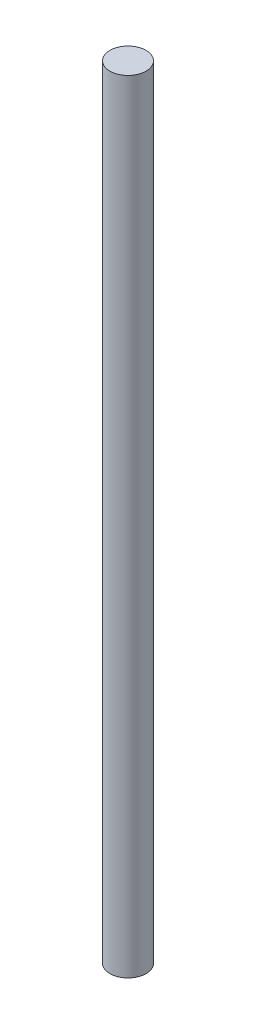
SolidWorks part; units mm, degrees
material "Сталь 20Х13Н4Г9 ГОСТ 5632-72"
ref_plane "Спереди" through (0, 0, 0) normal (0, 0, 1) x (1, 0, 0)
ref_plane "Сверху" through (0, 0, 0) normal (0, 1, 0) x (1, 0, 0)
ref_plane "Справа" through (0, 0, 0) normal (1, 0, 0) x (0, 0, -1)
other "Configuration Table"
sketch "Эскиз1" plane through (0, 0, 0) normal (0, 1, 0) x (1, 0, 0)
  circle A0 centre (0, 0) radius 3
  dimension "D1" = 6
extrude "Бобышка-Вытянуть1" add sketch "Эскиз1" along normal blind 130
